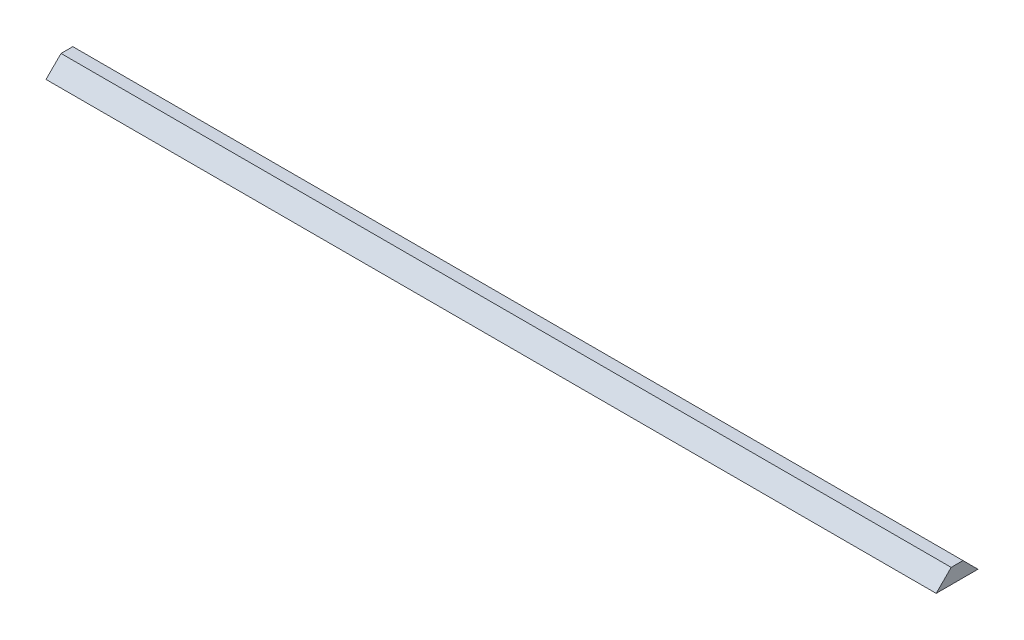
SolidWorks part; units mm, degrees
ref_plane "Front Plane" through (0, 0, 0) normal (0, 0, 1) x (1, 0, 0)
ref_plane "Top Plane" through (0, 0, 0) normal (0, 1, 0) x (1, 0, 0)
ref_plane "Right Plane" through (0, 0, 0) normal (1, 0, 0) x (0, 0, -1)
sketch "Sketch1" plane through (0, 0, 0) normal (1, 0, 0) x (0, 0, -1)
  line L3 (0, 0) -> (0, 1.4) construction
  line L5 (1.95, 0) -> (-1.95, 0)
  line L6 (-1.95, 0) -> (-0.55, 1.4)
  line L7 (-0.55, 1.4) -> (0.55, 1.4)
  line L8 (1.95, 0) -> (0.55, 1.4)
  point P7 (0, 1.4)
  dimension "D1" = 3.9
  dimension "D2" = 45
  dimension "D3" = 1.4
extrude "Boss-Extrude1" add sketch "Sketch1" along normal blind 83
